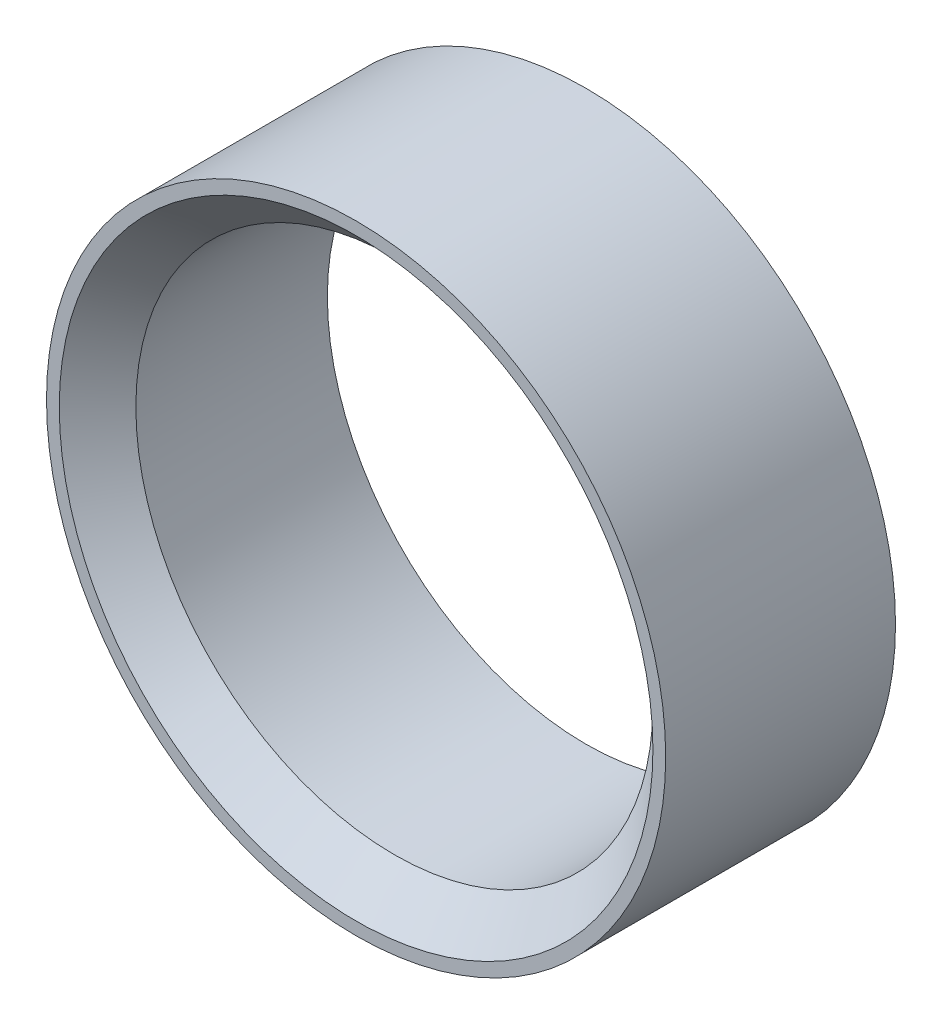
SolidWorks part; units mm, degrees
ref_plane "Plan de face" through (0, 0, 0) normal (0, 0, 1) x (1, 0, 0)
ref_plane "Plan de dessus" through (0, 0, 0) normal (0, 1, 0) x (1, 0, 0)
ref_plane "Plan de droite" through (0, 0, 0) normal (1, 0, 0) x (0, 0, -1)
sketch "Esquisse1" plane through (0, 0, 0) normal (0, 0, 1) x (1, 0, 0)
  circle A0 centre (0, 0) radius 20.25
  circle A1 centre (0, 0) radius 24.25
  dimension "D1" = 40.5
  dimension "D2" = 4
extrude "Boss.-Extru.1" add sketch "Esquisse1" along normal blind 48
chamfer "Chanfrein1" distance 3 angle 45 1 edges at (20.25, 0, 48)
sketch "Esquisse2" plane through (0, 0, 0) normal (0, 0, -1) x (-1, 0, 0)
  circle A0 centre (0, 0) radius 24.25
  circle A1 centre (0, 0) radius 24.25 construction
extrude "Enlèv. mat.-Extru.1" cut sketch "Esquisse2" against normal blind 30
